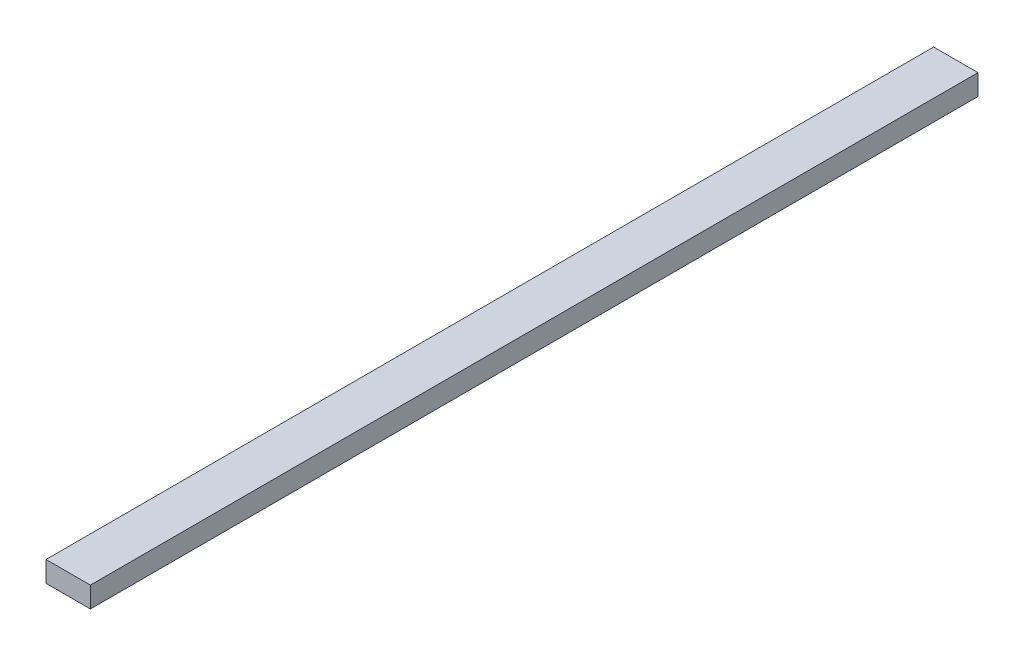
SolidWorks part; units mm, degrees
ref_plane "前视基准面" through (0, 0, 0) normal (0, 0, 1) x (1, 0, 0)
ref_plane "上视基准面" through (0, 0, 0) normal (0, 1, 0) x (1, 0, 0)
ref_plane "右视基准面" through (0, 0, 0) normal (1, 0, 0) x (0, 0, -1)
sketch "草图1" plane through (0, 0, 0) normal (0, 0, 1) x (1, 0, 0)
  line L1 (0, 0) -> (15, 0)
  line L2 (0, 0) -> (0, 7)
  line L3 (0, 7) -> (15, 7)
  line L4 (15, 0) -> (15, 7)
  dimension "D1" = 7
  dimension "D2" = 15
extrude "凸台-拉伸1" add sketch "草图1" along normal blind 300
